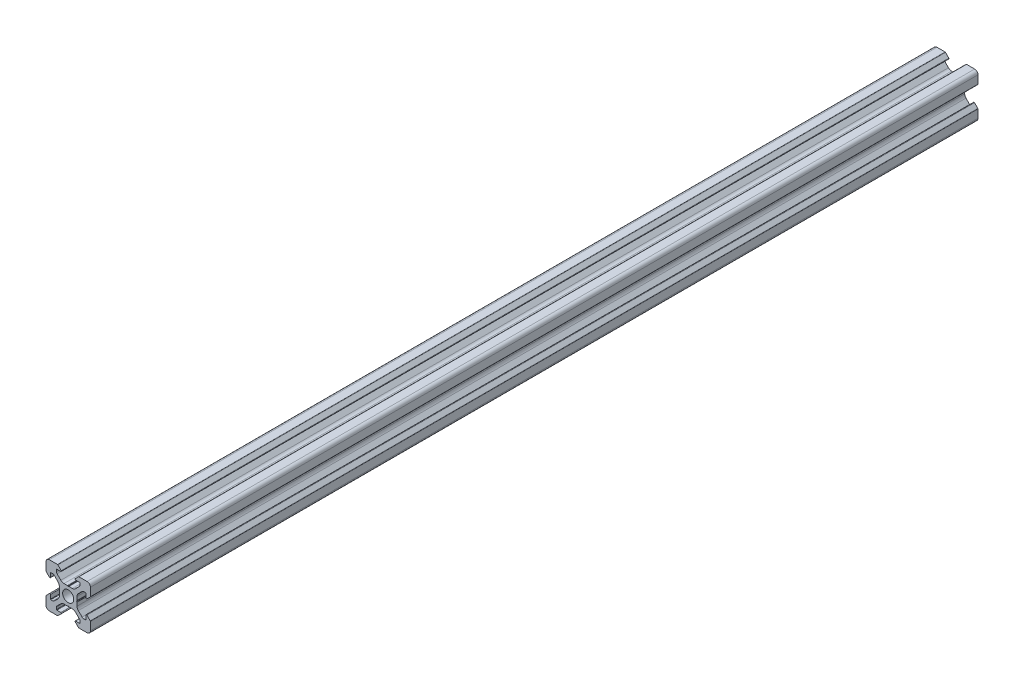
SolidWorks part; units mm, degrees
ref_plane "Спереди" through (0, 0, 0) normal (0, 0, 1) x (1, 0, 0)
ref_plane "Сверху" through (0, 0, 0) normal (0, 1, 0) x (1, 0, 0)
ref_plane "Справа" through (0, 0, 0) normal (1, 0, 0) x (0, 0, -1)
sketch "Model" plane through (0, 0, 0) normal (0, 0, 1) x (1, 0, 0)
  line L0 (-4, 0.3377) -> (-4, 1.8988)
  line L1 (-4.5858, 3.313) -> (-6.2799, 5.0071)
  line L2 (-6.987, 5.3) -> (-7.8, 5.3)
  line L3 (-8, 5.1) -> (-8, 3.33)
  line L4 (-9.9268, 4.6532) -> (-8.4268, 3.1532)
  line L5 (-10, 4.83) -> (-10, 8.5)
  line L6 (-4.6532, 9.9268) -> (-3.1532, 8.4268)
  line L7 (-0.1815, 3.9452) -> (0, 3.8)
  line L8 (0.1815, 3.9452) -> (0, 3.8)
  line L9 (0.3377, 4) -> (1.8988, 4)
  line L10 (3.313, 4.5858) -> (5.0071, 6.2799)
  line L11 (5.3, 6.987) -> (5.3, 7.8)
  line L12 (5.1, 8) -> (3.33, 8)
  line L13 (4.6532, 9.9268) -> (3.1532, 8.4268)
  line L14 (4.83, 10) -> (8.5, 10)
  line L15 (10, 4.83) -> (10, 8.5)
  line L16 (9.9268, 4.6532) -> (8.4268, 3.1532)
  line L17 (8, 5.1) -> (8, 3.33)
  line L18 (6.987, 5.3) -> (7.8, 5.3)
  line L19 (4.5858, 3.313) -> (6.2799, 5.0071)
  line L20 (4, 0.3377) -> (4, 1.8988)
  line L21 (3.9452, 0.1815) -> (3.8, 0)
  line L22 (3.9452, -0.1815) -> (3.8, 0)
  line L23 (4, -0.3377) -> (4, -1.8988)
  line L24 (4.5858, -3.313) -> (6.2799, -5.0071)
  line L25 (6.987, -5.3) -> (7.8, -5.3)
  line L26 (8, -5.1) -> (8, -3.33)
  line L27 (9.9268, -4.6532) -> (8.4268, -3.1532)
  line L28 (10, -4.83) -> (10, -8.5)
  line L29 (4.83, -10) -> (8.5, -10)
  line L30 (4.6532, -9.9268) -> (3.1532, -8.4268)
  line L31 (5.1, -8) -> (3.33, -8)
  line L32 (5.3, -6.987) -> (5.3, -7.8)
  line L33 (3.313, -4.5858) -> (5.0071, -6.2799)
  line L34 (0.3377, -4) -> (1.8988, -4)
  line L35 (0.1815, -3.9452) -> (0, -3.8)
  line L36 (-0.1815, -3.9452) -> (0, -3.8)
  line L37 (-3.313, -4.5858) -> (-5.0071, -6.2799)
  line L38 (-5.3, -6.987) -> (-5.3, -7.8)
  line L39 (-5.1, -8) -> (-3.33, -8)
  line L40 (-4.6532, -9.9268) -> (-3.1532, -8.4268)
  line L41 (-4.83, -10) -> (-8.5, -10)
  line L42 (-10, -4.83) -> (-10, -8.5)
  line L43 (-9.9268, -4.6532) -> (-8.4268, -3.1532)
  line L44 (-8, -5.1) -> (-8, -3.33)
  line L45 (-6.987, -5.3) -> (-7.8, -5.3)
  line L46 (-4.5858, -3.313) -> (-6.2799, -5.0071)
  line L47 (-4, -0.3377) -> (-4, -1.8988)
  line L48 (-3.9452, -0.1815) -> (-3.8, 0)
  line L49 (-3.9452, 0.1815) -> (-3.8, 0)
  line L50 (-0.3377, -4) -> (-1.8988, -4)
  line L51 (-0.3377, 4) -> (-1.8988, 4)
  line L52 (-3.313, 4.5858) -> (-5.0071, 6.2799)
  line L53 (-5.3, 6.987) -> (-5.3, 7.8)
  line L54 (-5.1, 8) -> (-3.33, 8)
  line L55 (-4.83, 10) -> (-8.5, 10)
  arc A0 (-4, 0.3377) -> (-3.9452, 0.1815) centre (-3.75, 0.3377) ccw
  arc A1 (-4, 1.8988) -> (-4.5858, 3.313) centre (-6, 1.8988) ccw
  arc A2 (-6.2799, 5.0071) -> (-6.987, 5.3) centre (-6.987, 4.3) ccw
  arc A3 (-7.8, 5.3) -> (-8, 5.1) centre (-7.8, 5.1) ccw
  arc A4 (-8.4268, 3.1532) -> (-8, 3.33) centre (-8.25, 3.33) ccw
  arc A5 (-10, 4.83) -> (-9.9268, 4.6532) centre (-9.75, 4.83) ccw
  arc A6 (-8.5, 10) -> (-10, 8.5) centre (-8.5, 8.5) ccw
  arc A7 (-4.6532, 9.9268) -> (-4.83, 10) centre (-4.83, 9.75) ccw
  arc A8 (-3.33, 8) -> (-3.1532, 8.4268) centre (-3.33, 8.25) ccw
  arc A9 (-5.1, 8) -> (-5.3, 7.8) centre (-5.1, 7.8) ccw
  arc A10 (-5.3, 6.987) -> (-5.0071, 6.2799) centre (-4.3, 6.987) ccw
  arc A11 (-3.313, 4.5858) -> (-1.8988, 4) centre (-1.8988, 6) ccw
  arc A12 (-0.1815, 3.9452) -> (-0.3377, 4) centre (-0.3377, 3.75) ccw
  arc A13 (0.3377, 4) -> (0.1815, 3.9452) centre (0.3377, 3.75) ccw
  arc A14 (1.8988, 4) -> (3.313, 4.5858) centre (1.8988, 6) ccw
  arc A15 (5.0071, 6.2799) -> (5.3, 6.987) centre (4.3, 6.987) ccw
  arc A16 (5.3, 7.8) -> (5.1, 8) centre (5.1, 7.8) ccw
  arc A17 (3.1532, 8.4268) -> (3.33, 8) centre (3.33, 8.25) ccw
  arc A18 (4.83, 10) -> (4.6532, 9.9268) centre (4.83, 9.75) ccw
  arc A19 (10, 8.5) -> (8.5, 10) centre (8.5, 8.5) ccw
  arc A20 (9.9268, 4.6532) -> (10, 4.83) centre (9.75, 4.83) ccw
  arc A21 (8, 3.33) -> (8.4268, 3.1532) centre (8.25, 3.33) ccw
  arc A22 (8, 5.1) -> (7.8, 5.3) centre (7.8, 5.1) ccw
  arc A23 (6.987, 5.3) -> (6.2799, 5.0071) centre (6.987, 4.3) ccw
  arc A24 (4.5858, 3.313) -> (4, 1.8988) centre (6, 1.8988) ccw
  arc A25 (3.9452, 0.1815) -> (4, 0.3377) centre (3.75, 0.3377) ccw
  arc A26 (4, -0.3377) -> (3.9452, -0.1815) centre (3.75, -0.3377) ccw
  arc A27 (4, -1.8988) -> (4.5858, -3.313) centre (6, -1.8988) ccw
  arc A28 (6.2799, -5.0071) -> (6.987, -5.3) centre (6.987, -4.3) ccw
  arc A29 (7.8, -5.3) -> (8, -5.1) centre (7.8, -5.1) ccw
  arc A30 (8.4268, -3.1532) -> (8, -3.33) centre (8.25, -3.33) ccw
  arc A31 (10, -4.83) -> (9.9268, -4.6532) centre (9.75, -4.83) ccw
  arc A32 (8.5, -10) -> (10, -8.5) centre (8.5, -8.5) ccw
  arc A33 (4.6532, -9.9268) -> (4.83, -10) centre (4.83, -9.75) ccw
  arc A34 (3.33, -8) -> (3.1532, -8.4268) centre (3.33, -8.25) ccw
  arc A35 (5.1, -8) -> (5.3, -7.8) centre (5.1, -7.8) ccw
  arc A36 (5.3, -6.987) -> (5.0071, -6.2799) centre (4.3, -6.987) ccw
  arc A37 (3.313, -4.5858) -> (1.8988, -4) centre (1.8988, -6) ccw
  arc A38 (0.1815, -3.9452) -> (0.3377, -4) centre (0.3377, -3.75) ccw
  arc A39 (-0.3377, -4) -> (-0.1815, -3.9452) centre (-0.3377, -3.75) ccw
  arc A40 (-1.8988, -4) -> (-3.313, -4.5858) centre (-1.8988, -6) ccw
  arc A41 (-5.0071, -6.2799) -> (-5.3, -6.987) centre (-4.3, -6.987) ccw
  arc A42 (-5.3, -7.8) -> (-5.1, -8) centre (-5.1, -7.8) ccw
  arc A43 (-3.1532, -8.4268) -> (-3.33, -8) centre (-3.33, -8.25) ccw
  arc A44 (-4.83, -10) -> (-4.6532, -9.9268) centre (-4.83, -9.75) ccw
  arc A45 (-10, -8.5) -> (-8.5, -10) centre (-8.5, -8.5) ccw
  arc A46 (-9.9268, -4.6532) -> (-10, -4.83) centre (-9.75, -4.83) ccw
  arc A47 (-8, -3.33) -> (-8.4268, -3.1532) centre (-8.25, -3.33) ccw
  arc A48 (-8, -5.1) -> (-7.8, -5.3) centre (-7.8, -5.1) ccw
  arc A49 (-6.987, -5.3) -> (-6.2799, -5.0071) centre (-6.987, -4.3) ccw
  arc A50 (-4.5858, -3.313) -> (-4, -1.8988) centre (-6, -1.8988) ccw
  arc A51 (-3.9452, -0.1815) -> (-4, -0.3377) centre (-3.75, -0.3377) ccw
  circle A52 centre (0, 0) radius 2.5
extrude "Бобышка-Вытянуть1" add sketch "Model" along normal blind 400
